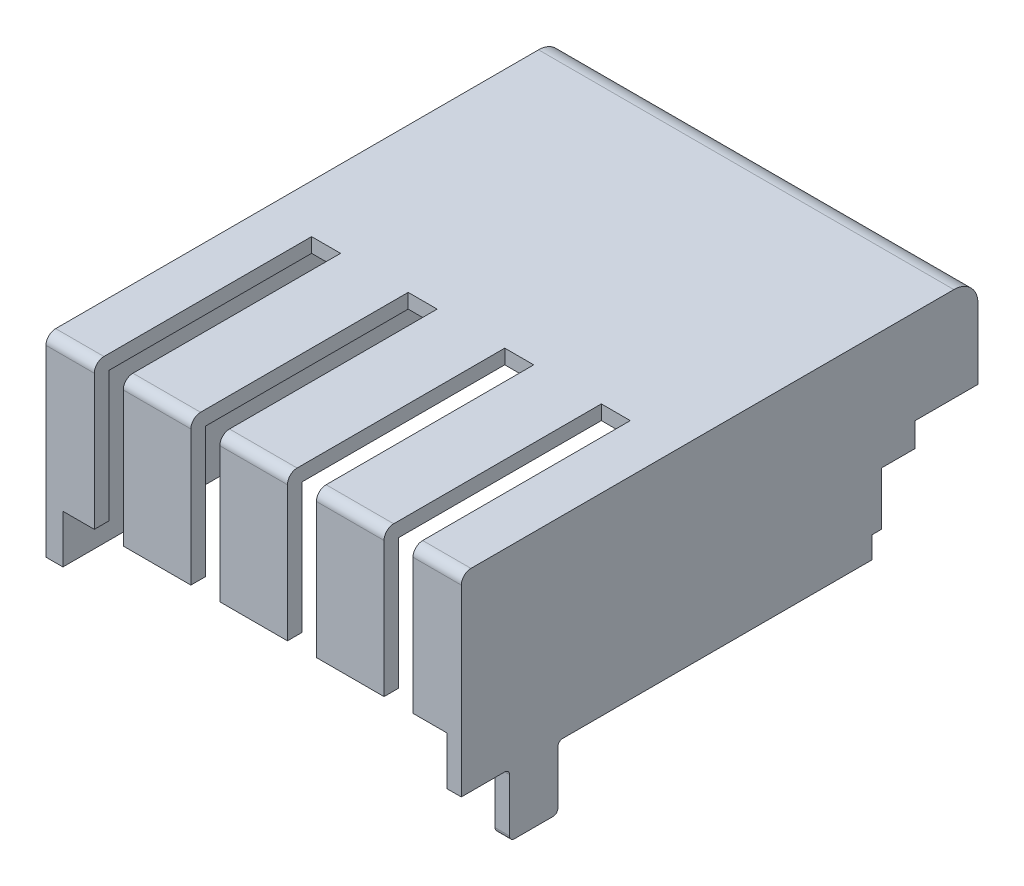
SolidWorks part; units mm, degrees
ref_plane "Alzado" through (0, 0, 0) normal (0, 0, 1) x (1, 0, 0)
ref_plane "Planta" through (0, 0, 0) normal (0, 1, 0) x (1, 0, 0)
ref_plane "Vista lateral" through (0, 0, 0) normal (1, 0, 0) x (0, 0, -1)
sketch "Croquis1" plane through (0, 0, 0) normal (0, 0, 1) x (1, 0, 0)
  line L0 (-42, 0) -> (-45, 0)
  line L1 (-42, 37) -> (42, 37)
  line L2 (-42, 37) -> (-42, 0)
  line L3 (-42, 0) -> (42, 0) construction
  line L4 (42, 37) -> (42, 0)
  line L5 (-45, 0) -> (-45, 40)
  line L6 (-45, 40) -> (45, 40)
  line L7 (45, 40) -> (45, 0)
  line L8 (45, 0) -> (42, 0)
  line L9 (0, 0) -> (0, 37) construction
  point P4 (0, 0)
  dimension "D1" = 84
  dimension "D2" = 37
  dimension "D3" = 3
  dimension "D4" = 3
extrude "Saliente-Extruir1" add sketch "Croquis1" against normal blind 107
sketch "Croquis2" plane through (0, 0, -107) normal (0, 0, -1) x (-1, 0, 0)
  line L0 (45, 40) -> (45, 0) construction
  line L5 (-45, 40) -> (45, 40)
  line L6 (-45, 40) -> (-45, 22)
  line L7 (-45, 22) -> (45, 22)
  line L8 (45, 40) -> (45, 22)
  dimension "D1" = 18
extrude "Saliente-Extruir2" add sketch "Croquis2" against normal blind 3
sketch "Croquis4" plane through (0, 0, 0) normal (0, 0, 1) x (1, 0, 0)
  line L0 (45, 0) -> (45, 40) construction
  line L1 (-45, 40) -> (45, 40)
  line L2 (-45, 40) -> (-45, 10)
  line L3 (-45, 10) -> (45, 10)
  line L4 (45, 40) -> (45, 10)
  dimension "D1" = 30
extrude "Saliente-Extruir3" add sketch "Croquis4" against normal blind 3
fillet "Redondeo3" radius 2 1 edges at (0, 40, 0)
sketch "Croquis3" plane through (0, 40, 0) normal (0, 1, 0) x (1, 0, 0)
  line L0 (45, 0) -> (-45, 0) construction
  line L1 (-6, 0) -> (-12, 0)
  line L2 (-6, 0) -> (-6, 45)
  line L3 (-6, 45) -> (-12, 45)
  line L4 (-12, 0) -> (-12, 45)
  line L5 (1, 0) -> (1, 50) construction
  line L6 (8, 0) -> (14, 0)
  line L7 (8, 0) -> (8, 45)
  line L8 (8, 45) -> (14, 45)
  line L9 (14, 0) -> (14, 45)
  line L11 (-26, 0) -> (-26, 45)
  line L12 (-26, 0) -> (-32, 0)
  line L13 (-32, 0) -> (-32, 45)
  line L14 (-26, 45) -> (-32, 45)
  line L15 (28, 0) -> (28, 45)
  line L16 (28, 0) -> (34, 0)
  line L17 (34, 0) -> (34, 45)
  line L18 (28, 45) -> (34, 45)
  point P14 (-9, 0)
  point P15 (11, 0)
  point P17 (-29, 0)
  dimension "D1" = 20
  dimension "D2" = 45
  dimension "D3" = 6
  dimension "D4" = 2
  dimension "D6" = 20
  dimension "D7" = 1
  dimension "D8" = 50
  dimension "D5" = 2
extrude "Cortar-Extruir1" cut sketch "Croquis3" against normal through all
fillet "Redondeo1" radius 5 1 edges at (0, 40, -107)
sketch "Croquis6" plane through (-42, 0, 0) normal (1, 0, 0) x (0, 0, -1)
  line L8 (3, 10) -> (0, 10)
  line L9 (0, 10) -> (0, 0)
  line L10 (0, 0) -> (107, 0)
  line L11 (107, 0) -> (107, 22)
  line L12 (107, 22) -> (104, 22)
  line L13 (104, 22) -> (104, 37)
  line L14 (104, 37) -> (3, 37)
  line L15 (3, 37) -> (3, 10)
  line L16 (3, 10) -> (0, 10)
  line L17 (0, 10) -> (0, 0)
  line L18 (0, 0) -> (107, 0)
  line L19 (107, 0) -> (107, 22)
  line L20 (107, 22) -> (104, 22)
  line L21 (104, 22) -> (104, 37)
  line L22 (104, 37) -> (3, 37)
  line L23 (3, 37) -> (3, 10)
  dimension "D1" = 0
extrude "Saliente-Extruir4" add sketch "Croquis6" along normal blind 3.5
sketch "Croquis7" plane through (-45, 0, 0) normal (-1, 0, 0) x (0, 0, 1)
  line L4 (-2, 40) -> (-102, 40)
  line L5 (-107, 35) -> (-107, 0)
  line L6 (-107, 0) -> (0, 0)
  line L7 (0, 0) -> (0, 38)
  line L8 (-2, 40) -> (-102, 40)
  line L9 (-107, 35) -> (-107, 0)
  line L10 (-107, 0) -> (0, 0)
  line L11 (0, 0) -> (0, 38)
  arc A2 (-102, 40) -> (-107, 35) centre (-102, 35) ccw
  arc A3 (0, 38) -> (-2, 40) centre (-2, 38) ccw
  arc A4 (-102, 40) -> (-107, 35) centre (-102, 35) ccw
  arc A5 (0, 38) -> (-2, 40) centre (-2, 38) ccw
  dimension "D1" = 0
extrude "Cortar-Extruir3" cut sketch "Croquis7" against normal blind 3
sketch "Croquis8" plane through (-42, 0, 0) normal (-1, 0, 0) x (0, 0, 1)
  line L0 (-107, 0) -> (0, 0) construction
  line L1 (-107, 0) -> (-94, 0)
  line L2 (-107, 0) -> (-107, 20.5)
  line L3 (-107, 20.5) -> (-94, 20.5)
  line L4 (-94, 15.5) -> (-94, 20.5)
  line L5 (-94, 15.5) -> (-87, 15.5)
  line L7 (-94, 0) -> (-87, 0)
  line L8 (-87, 15.5) -> (-87, 4.5)
  line L10 (-87, 4.5) -> (-85, 4.5)
  line L12 (-87, 0) -> (-85, 0)
  line L13 (-85, 4.5) -> (-85, 0)
  dimension "D1" = 20.5
  dimension "D2" = 13
  dimension "D3" = 15.5
  dimension "D4" = 7
  dimension "D5" = 4.5
  dimension "D6" = 2
extrude "Cortar-Extruir4" cut sketch "Croquis8" against normal through all
sketch "Croquis9" plane through (45, 0, 0) normal (1, 0, 0) x (0, 0, -1)
  line L0 (85, 0) -> (0, 0) construction
  line L1 (10, 0) -> (20, 0)
  line L2 (10, 0) -> (10, -12)
  line L3 (11, -13) -> (19, -13)
  line L4 (20, 0) -> (20, -12)
  line L5 (0, 0) -> (0, 38) construction
  arc A0 (19, -13) -> (20, -12) centre (19, -12) ccw
  arc A1 (10, -12) -> (11, -13) centre (11, -12) ccw
  dimension "D4" = 1
  dimension "D1" = 10
  dimension "D2" = 10
  dimension "D3" = 13
extrude "Saliente-Extruir5" add sketch "Croquis9" against normal blind 3
sketch "Croquis10" plane through (45, 0, 0) normal (1, 0, 0) x (0, 0, -1)
  line L0 (11, -13) -> (19, -13) construction
  circle A0 centre (15, -9) radius 1.5
  point P4 (15, -13)
  dimension "D2" = 3
  dimension "D1" = 4
fillet "Redondeo4" radius 1 2 edges at (43.5, 0, -20) (43.5, 0, -10)
sketch "Croquis11" plane through (42, 0, 0) normal (-1, 0, 0) x (0, 0, 1)
  line L18 (-107, 20.5) -> (-94, 20.5)
  line L19 (-94, 20.5) -> (-94, 15.5)
  line L20 (-94, 15.5) -> (-87, 15.5)
  line L21 (-87, 15.5) -> (-87, 4.5)
  line L22 (-87, 4.5) -> (-85, 4.5)
  line L23 (-85, 4.5) -> (-85, 0)
  line L24 (-85, 0) -> (-21, 0)
  line L25 (-20, -1) -> (-20, -12)
  line L26 (-19, -13) -> (-11, -13)
  line L27 (-10, -12) -> (-10, -1)
  line L28 (-9, 0) -> (0, 0)
  line L29 (0, 0) -> (0, 10)
  line L30 (0, 10) -> (-3, 10)
  line L31 (-3, 10) -> (-3, 37)
  line L32 (-3, 37) -> (-104, 37)
  line L33 (-104, 37) -> (-104, 22)
  line L34 (-104, 22) -> (-107, 22)
  line L35 (-107, 22) -> (-107, 20.5)
  line L36 (-107, 20.5) -> (-94, 20.5)
  line L37 (-94, 20.5) -> (-94, 15.5)
  line L38 (-94, 15.5) -> (-87, 15.5)
  line L39 (-87, 15.5) -> (-87, 4.5)
  line L40 (-87, 4.5) -> (-85, 4.5)
  line L41 (-85, 4.5) -> (-85, 0)
  line L42 (-85, 0) -> (-21, 0)
  line L43 (-20, -1) -> (-20, -12)
  line L44 (-19, -13) -> (-11, -13)
  line L45 (-10, -12) -> (-10, -1)
  line L46 (-9, 0) -> (0, 0)
  line L47 (0, 0) -> (0, 10)
  line L48 (0, 10) -> (-3, 10)
  line L49 (-3, 10) -> (-3, 37)
  line L50 (-3, 37) -> (-104, 37)
  line L51 (-104, 37) -> (-104, 22)
  line L52 (-104, 22) -> (-107, 22)
  line L53 (-107, 22) -> (-107, 20.5)
  arc A4 (-20, -1) -> (-21, 0) centre (-21, -1) ccw
  arc A5 (-20, -12) -> (-19, -13) centre (-19, -12) ccw
  arc A6 (-11, -13) -> (-10, -12) centre (-11, -12) ccw
  arc A7 (-9, 0) -> (-10, -1) centre (-9, -1) ccw
  arc A8 (-20, -1) -> (-21, 0) centre (-21, -1) ccw
  arc A9 (-20, -12) -> (-19, -13) centre (-19, -12) ccw
  arc A10 (-11, -13) -> (-10, -12) centre (-11, -12) ccw
  arc A11 (-9, 0) -> (-10, -1) centre (-9, -1) ccw
  dimension "D1" = 0
extrude "Saliente-Extruir6" add sketch "Croquis11" along normal blind 1
sketch "Croquis12" plane through (45, 0, 0) normal (1, 0, 0) x (0, 0, -1)
  line L14 (94, 20.5) -> (107, 20.5)
  line L15 (107, 20.5) -> (107, 35)
  line L16 (102, 40) -> (2, 40)
  line L17 (0, 38) -> (0, 0)
  line L18 (0, 0) -> (9, 0)
  line L19 (10, -1) -> (10, -12)
  line L20 (11, -13) -> (19, -13)
  line L21 (20, -12) -> (20, -1)
  line L22 (21, 0) -> (85, 0)
  line L23 (85, 0) -> (85, 4.5)
  line L24 (85, 4.5) -> (87, 4.5)
  line L25 (87, 4.5) -> (87, 15.5)
  line L26 (87, 15.5) -> (94, 15.5)
  line L27 (94, 15.5) -> (94, 20.5)
  line L28 (94, 20.5) -> (107, 20.5)
  line L29 (107, 20.5) -> (107, 35)
  line L30 (102, 40) -> (2, 40)
  line L31 (0, 38) -> (0, 0)
  line L32 (0, 0) -> (9, 0)
  line L33 (10, -1) -> (10, -12)
  line L34 (11, -13) -> (19, -13)
  line L35 (20, -12) -> (20, -1)
  line L36 (21, 0) -> (85, 0)
  line L37 (85, 0) -> (85, 4.5)
  line L38 (85, 4.5) -> (87, 4.5)
  line L39 (87, 4.5) -> (87, 15.5)
  line L40 (87, 15.5) -> (94, 15.5)
  line L41 (94, 15.5) -> (94, 20.5)
  arc A6 (107, 35) -> (102, 40) centre (102, 35) ccw
  arc A7 (2, 40) -> (0, 38) centre (2, 38) ccw
  arc A8 (10, -1) -> (9, 0) centre (9, -1) ccw
  arc A9 (10, -12) -> (11, -13) centre (11, -12) ccw
  arc A10 (19, -13) -> (20, -12) centre (19, -12) ccw
  arc A11 (21, 0) -> (20, -1) centre (21, -1) ccw
  arc A12 (107, 35) -> (102, 40) centre (102, 35) ccw
  arc A13 (2, 40) -> (0, 38) centre (2, 38) ccw
  arc A14 (10, -1) -> (9, 0) centre (9, -1) ccw
  arc A15 (10, -12) -> (11, -13) centre (11, -12) ccw
  arc A16 (19, -13) -> (20, -12) centre (19, -12) ccw
  arc A17 (21, 0) -> (20, -1) centre (21, -1) ccw
  dimension "D1" = 0
extrude "Cortar-Extruir6" cut sketch "Croquis12" against normal blind 1
